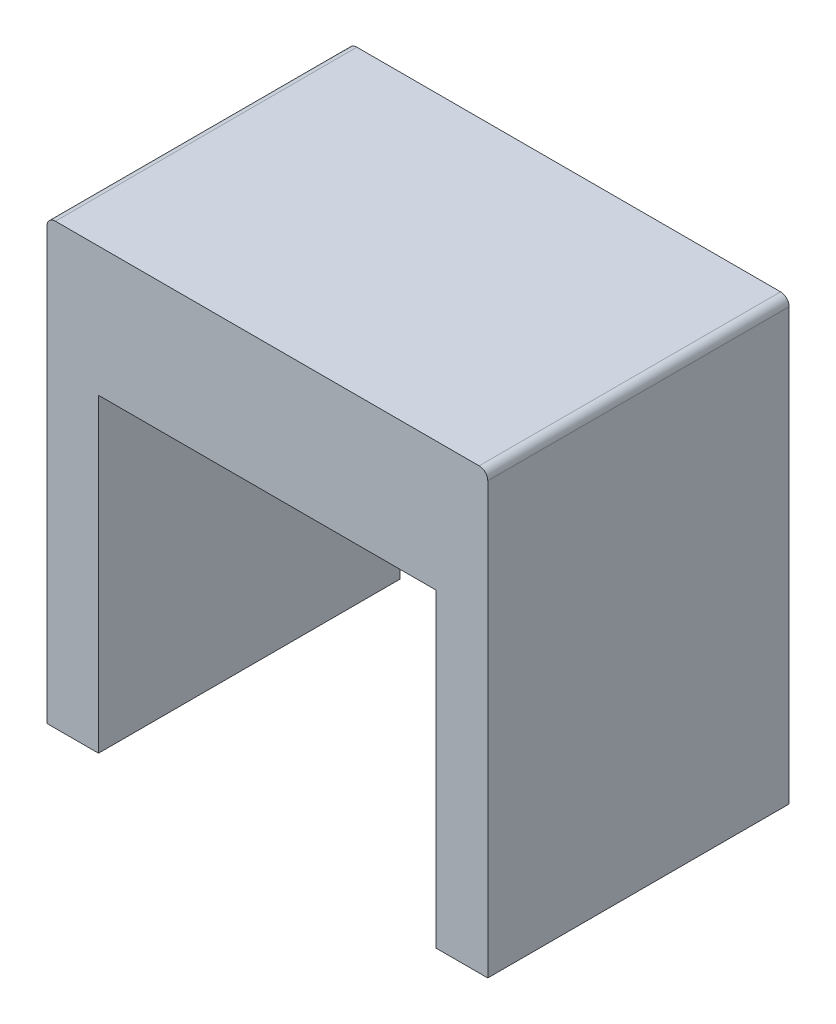
SolidWorks part; units mm, degrees
ref_plane "Front Plane" through (0, 0, 0) normal (0, 0, 1) x (1, 0, 0)
ref_plane "Top Plane" through (0, 0, 0) normal (0, 1, 0) x (1, 0, 0)
ref_plane "Right Plane" through (0, 0, 0) normal (1, 0, 0) x (0, 0, -1)
sketch "Sketch1" plane through (0, 0, 0) normal (0, 0, 1) x (1, 0, 0)
  line L0 (-25.3408, -40.8813) -> (-25.3408, -4.8813)
  line L1 (-25.3408, -4.8813) -> (13.8592, -4.8813)
  line L2 (13.8592, -4.8813) -> (13.8592, -40.8813)
  line L3 (13.8592, -40.8813) -> (19.8592, -40.8813)
  line L4 (19.8592, -40.8813) -> (19.8592, 10.1187)
  line L5 (19.8592, 10.1187) -> (-31.3408, 10.1187)
  line L6 (-31.3408, 10.1187) -> (-31.3408, -40.8813)
  line L7 (-31.3408, -40.8813) -> (-25.3408, -40.8813)
  dimension "D1" = 39.2
  dimension "D2" = 6
  dimension "D3" = 15
  dimension "D4" = 36
extrude "Boss-Extrude1" add sketch "Sketch1" along normal blind 35
fillet "Fillet1" radius 1 2 edges at (19.8592, 10.1187, 17.5) (-31.3408, 10.1187, 17.5)
